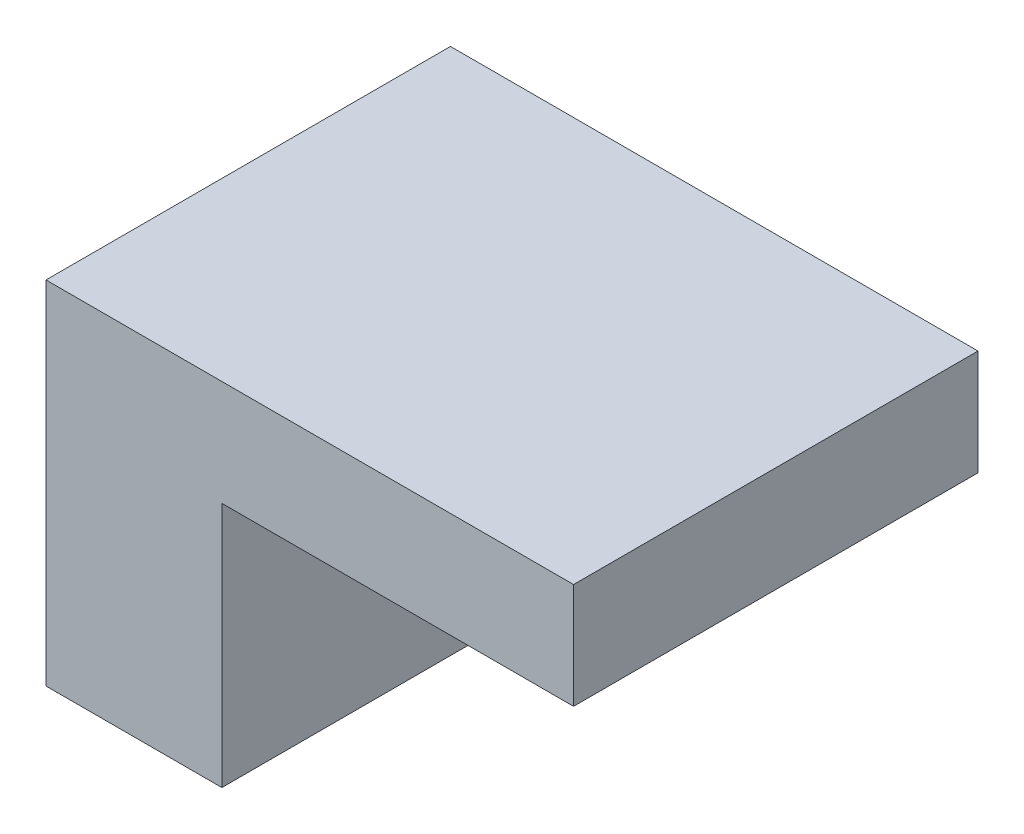
SolidWorks part; units mm, degrees
ref_plane "Front Plane" through (0, 0, 0) normal (0, 0, 1) x (1, 0, 0)
ref_plane "Top Plane" through (0, 0, 0) normal (0, 1, 0) x (1, 0, 0)
ref_plane "Right Plane" through (0, 0, 0) normal (1, 0, 0) x (0, 0, -1)
sketch "Sketch1" plane through (0, 0, 0) normal (0, 0, 1) x (1, 0, 0)
  line L0 (0, 0) -> (0, 100)
  line L1 (0, 100) -> (150, 100)
  line L2 (150, 100) -> (150, 70)
  line L3 (150, 70) -> (50, 70)
  line L4 (50, 70) -> (50, 0)
  line L5 (50, 0) -> (0, 0)
extrude "Boss-Extrude1" add sketch "Sketch1" along normal blind 115
ref_plane "Plane1" through (0, 0, 57.5) normal (0, 0, 1) x (1, 0, 0)
sketch "Sketch2" plane through (0, 0, 57.5) normal (0, 0, 1) x (1, 0, 0)
  line L0 (25.6084, 6.375) -> (130.9103, 83.0949)
rib "Rib1" sketch "Sketch2" sketch "Sketch2" thickness 10 extrusion direction parallel to sketch draft on no parameters "D1"=10
